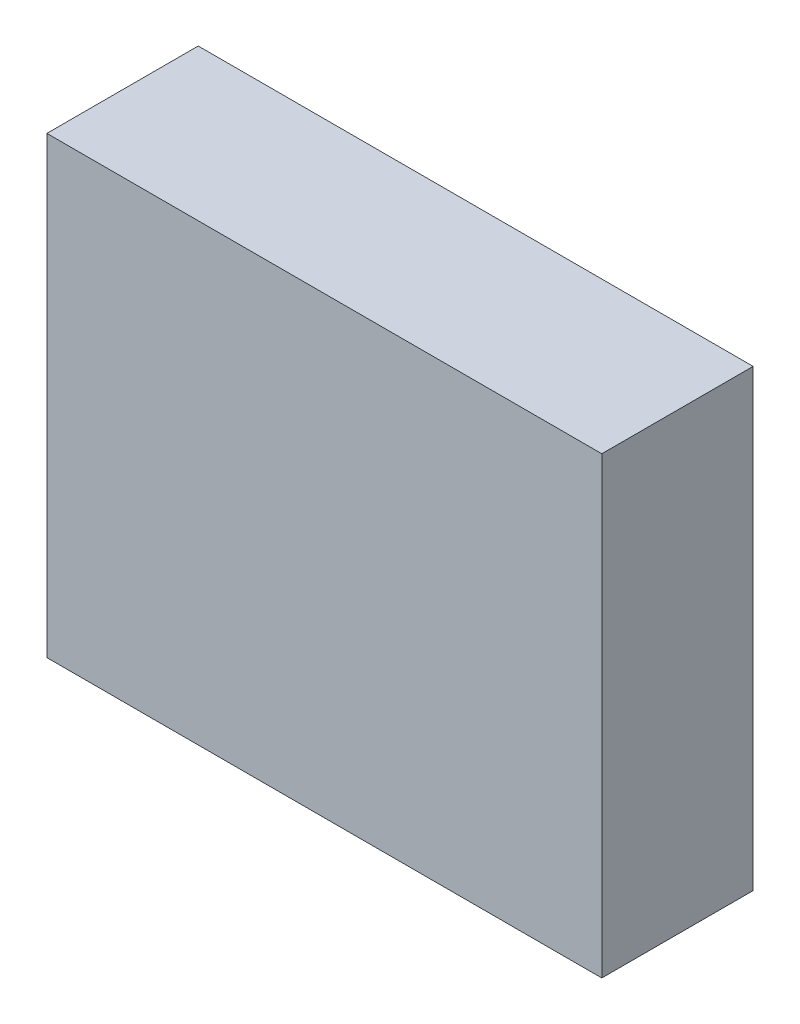
SolidWorks part; units mm, degrees
ref_plane "Front Plane" through (0, 0, 0) normal (0, 0, 1) x (1, 0, 0)
ref_plane "Top Plane" through (0, 0, 0) normal (0, 1, 0) x (1, 0, 0)
ref_plane "Right Plane" through (0, 0, 0) normal (1, 0, 0) x (0, 0, -1)
other "Configuration Table"
sketch "Sketch1" plane through (0, 0, 0) normal (0, 0, 1) x (1, 0, 0)
  line L1 (990, 1690) -> (1100, 1690)
  line L2 (990, 1690) -> (990, 1780)
  line L3 (990, 1780) -> (1100, 1780)
  line L4 (1100, 1690) -> (1100, 1780)
extrude "STORE_pano_role_karti_1_8kanal_1" add sketch "Sketch1" against normal blind 30 from offset 670 separate body
